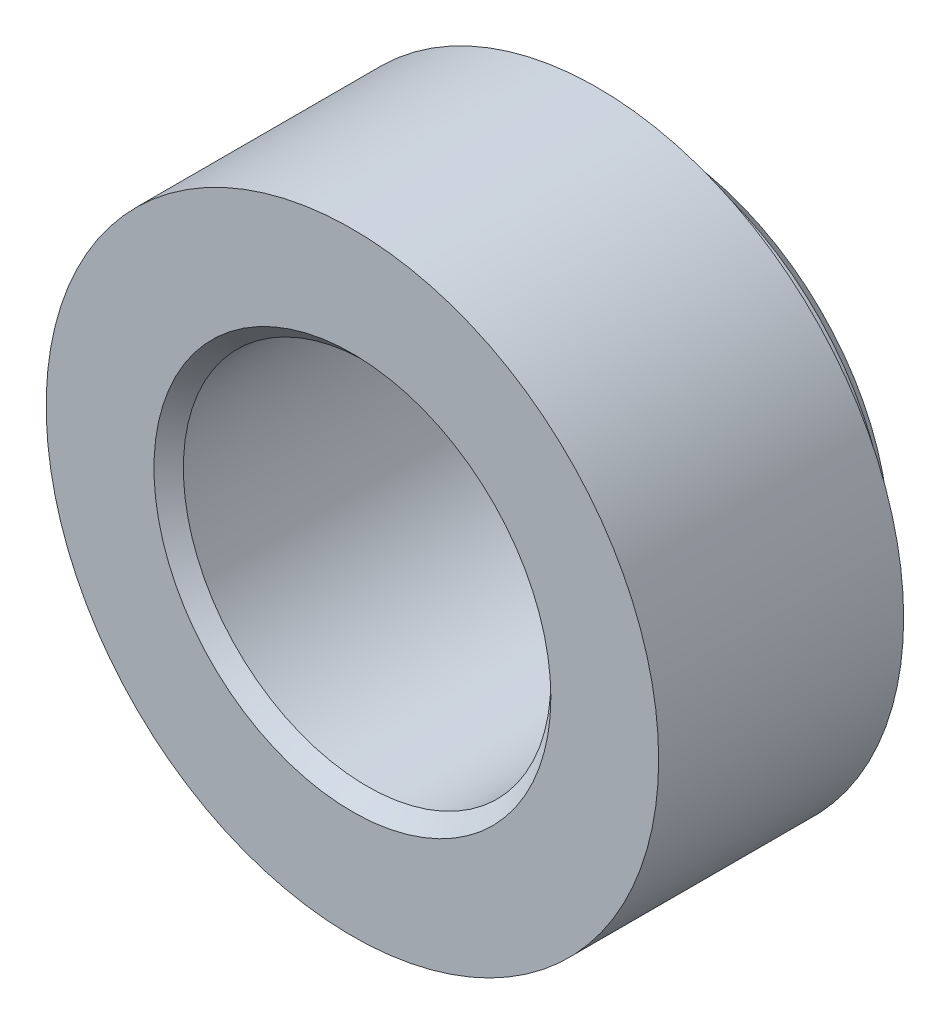
SolidWorks part; units mm, degrees
material "Plain Carbon Steel"
ref_plane "Front Plane" through (0, 0, 0) normal (0, 0, 1) x (1, 0, 0)
ref_plane "Top Plane" through (0, 0, 0) normal (0, 1, 0) x (1, 0, 0)
ref_plane "Right Plane" through (0, 0, 0) normal (1, 0, 0) x (0, 0, -1)
sketch "Sketch1" plane through (0, 0, 0) normal (1, 0, 0) x (0, 0, -1)
  line L0 (0, 0) -> (39.1548, 0) construction
  line L1 (0, 31.75) -> (0, 20.574)
  line L2 (0, 20.574) -> (1.524, 19.05)
  line L3 (1.524, 19.05) -> (31.75, 19.05)
  line L4 (31.75, 19.05) -> (31.75, 23.876)
  line L5 (31.75, 23.876) -> (30.226, 25.4)
  line L6 (30.226, 25.4) -> (25.4, 25.4)
  line L7 (25.4, 25.4) -> (25.4, 31.75)
  line L8 (25.4, 31.75) -> (0, 31.75)
  point P5 (28.2691, 25.4)
  dimension "D1" = 50.8
  dimension "D2" = 6.35
  dimension "D3" = 31.75
  dimension "D4" = 63.5
  dimension "D5" = 38.1
  dimension "D6" = 45
  dimension "D7" = 45
  dimension "D8" = 1.524
  dimension "D9" = 1.524
revolve "Revolve1" add sketch "Sketch1" angle 360 about L0
